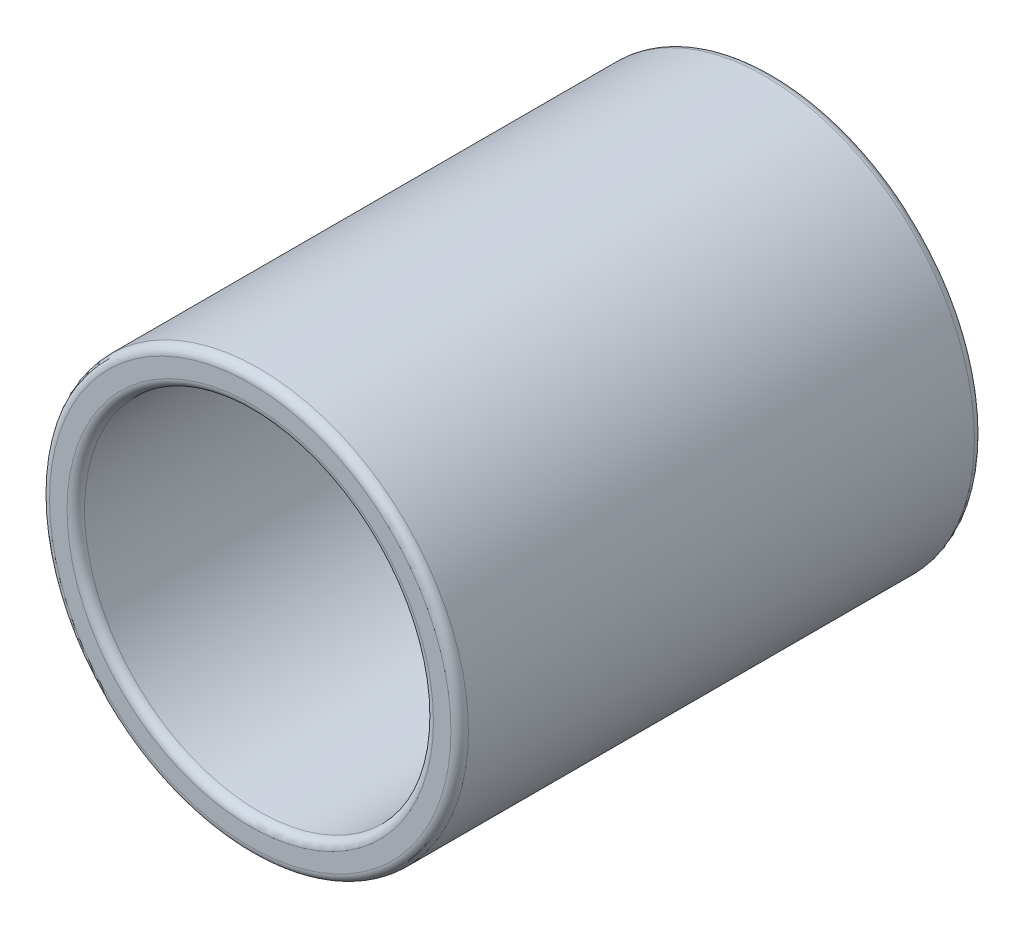
SolidWorks part; units mm, degrees
ref_plane "Plan1" through (0, 0, 0) normal (0, 0, 1) x (1, 0, 0)
ref_plane "Plan2" through (0, 0, 0) normal (0, 1, 0) x (1, 0, 0)
ref_plane "Plan3" through (0, 0, 0) normal (1, 0, 0) x (0, 0, -1)
sketch "Esquisse1" plane through (0, 0, 0) normal (0, 0, 1) x (1, 0, 0)
  circle A0 centre (0, 0) radius 12
  circle A1 centre (0, 0) radius 10
  dimension "D1" = 20
  dimension "D2" = 24
extrude "Base-Extrusion" add sketch "Esquisse1" along normal blind 30
fillet "Congé1" radius 0.5
